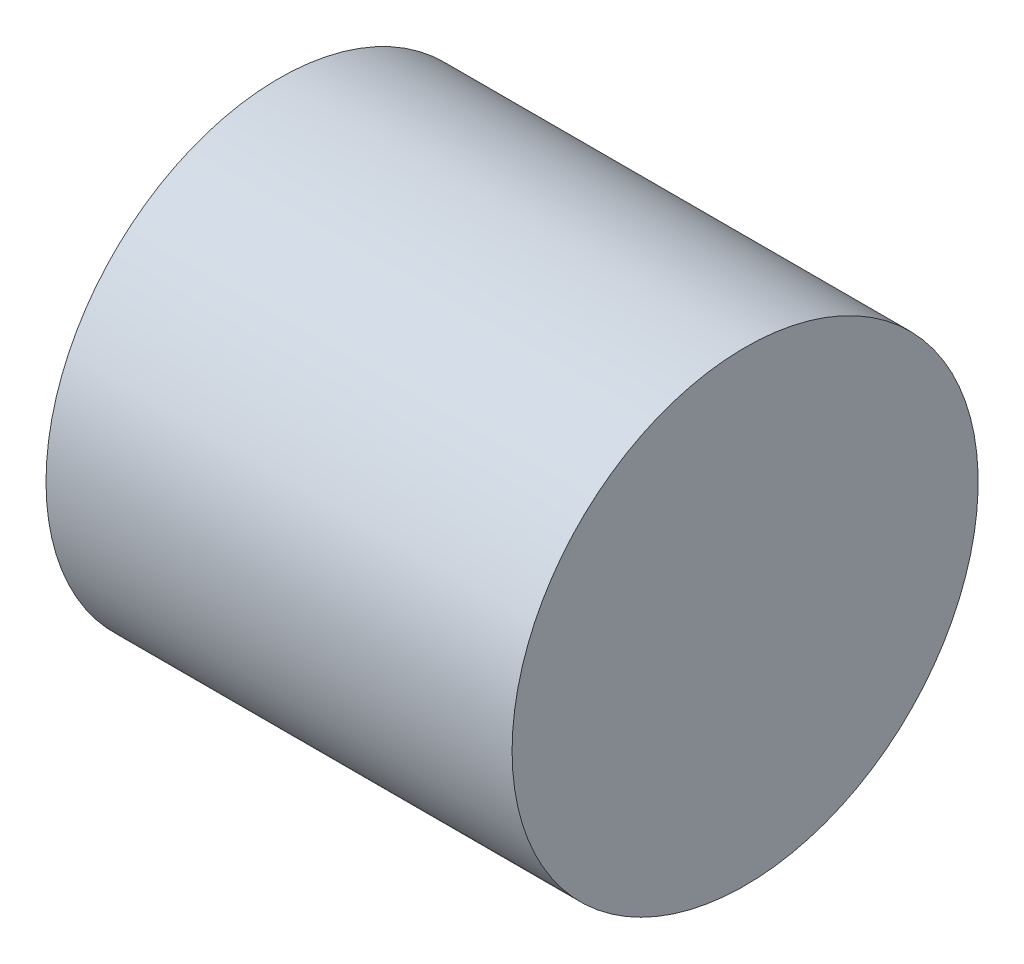
SolidWorks part; units mm, degrees
ref_plane "Front Plane" through (0, 0, 0) normal (0, 0, 1) x (1, 0, 0)
ref_plane "Top Plane" through (0, 0, 0) normal (0, 1, 0) x (1, 0, 0)
ref_plane "Right Plane" through (0, 0, 0) normal (1, 0, 0) x (0, 0, -1)
sketch "Sketch1" plane through (0, 0, 0) normal (0, 0, 1) x (1, 0, 0)
  line L0 (0, 0) -> (584.2, 0)
  line L1 (0, 0) -> (0, 292.1)
  line L3 (0, 292.1) -> (584.2, 292.1)
  line L5 (584.2, 292.1) -> (584.2, 0)
  point P3 (0, 0)
  point P7 (0, 292.1)
  point P8 (576.8037, 292.1)
  point P9 (0, 284.963)
  dimension "D1" = 292.1
  dimension "D2" = 584.2
revolve "Revolve1" add sketch "Sketch1" angle 360 about L0
